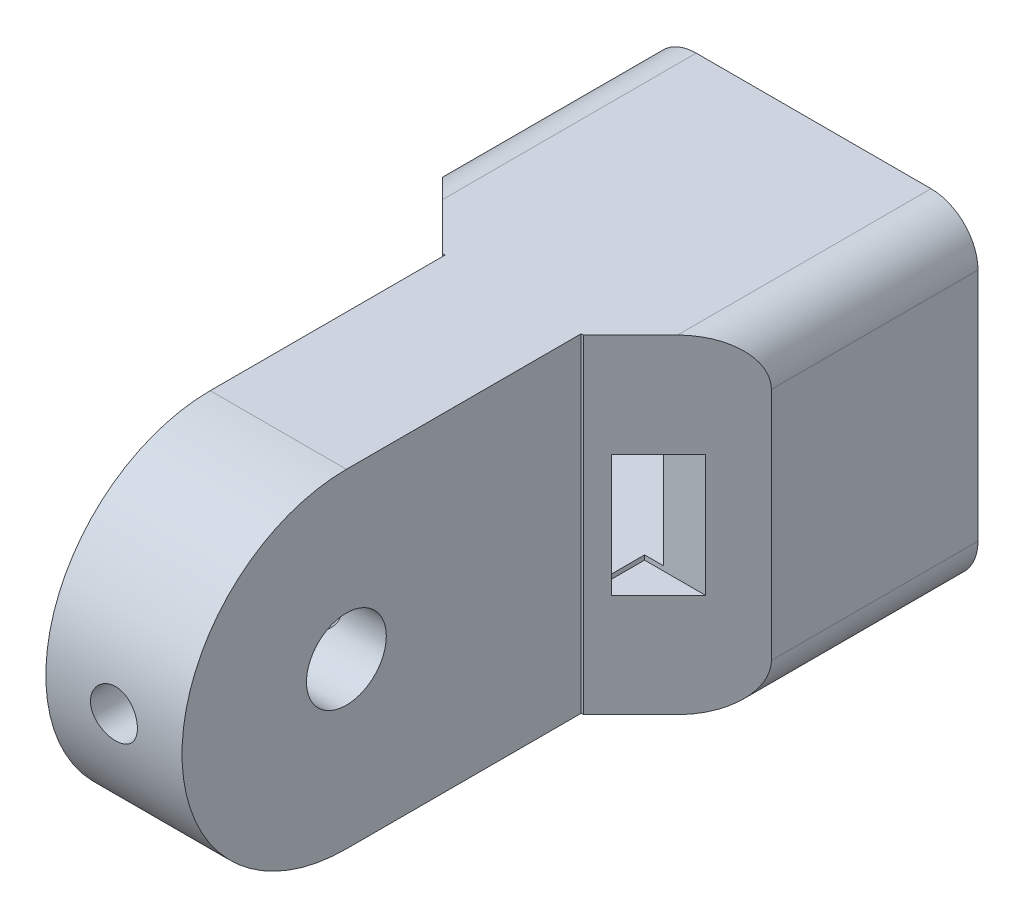
SolidWorks part; units mm, degrees
ref_plane "Alzado" through (0, 0, 0) normal (0, 0, 1) x (1, 0, 0)
ref_plane "Planta" through (0, 0, 0) normal (0, 1, 0) x (1, 0, 0)
ref_plane "Vista lateral" through (0, 0, 0) normal (1, 0, 0) x (0, 0, -1)
sketch "Croquis6" plane through (0, 0, 0) normal (1, 0, 0) x (0, 0, -1)
  line L0 (0, 17.5) -> (25, 17.5)
  line L1 (0, -17.5) -> (25, -17.5)
  line L2 (25, 17.5) -> (25, -17.5)
  circle A0 centre (0, 0) radius 4.25
  arc A1 (0, 17.5) -> (0, -17.5) centre (0, 0) ccw
  dimension "D1" = 8.5
  dimension "D2" = 35
  dimension "D3" = 25
extrude "Saliente-Extruir2" add sketch "Croquis6" along normal mid plane 14.5
sketch "Croquis7" plane through (0, 0, -25) normal (0, 0, -1) x (-1, 0, 0)
  line L1 (-17.5, -17.5) -> (17.5, -17.5)
  line L2 (-17.5, -17.5) -> (-17.5, 17.5)
  line L3 (-17.5, 17.5) -> (17.5, 17.5)
  line L4 (17.5, -17.5) -> (17.5, 17.5)
  line L5 (-17.5, -17.5) -> (17.5, 17.5) construction
  line L6 (-17.5, 17.5) -> (17.5, -17.5) construction
  point P0 (0, 0)
  dimension "D1" = 35
extrude "Saliente-Extruir3" add sketch "Croquis7" along normal blind 32
chamfer "Chaflán1" distance 10 angle 45 2 edges at (-17.5, 0, -25) (17.5, 0, -25)
sketch "Croquis8" plane through (0, 0, -57) normal (0, 0, -1) x (-1, 0, 0)
  line L1 (-5, -6.015) -> (5, -6.015) construction
  line L2 (-5, -6.015) -> (-5, 6.015) construction
  line L3 (-5, 6.015) -> (5, 6.015) construction
  line L4 (5, -6.015) -> (5, 6.015) construction
  line L5 (-5, -6.015) -> (5, 6.015) construction
  line L6 (-5, 6.015) -> (5, -6.015) construction
  line L7 (5, -6.015) -> (-9.5, -6.015)
  line L8 (5, -6.015) -> (5, 6.015)
  line L9 (5, 6.015) -> (-9.5, 6.015)
  line L10 (-9.5, -6.015) -> (-9.5, 6.015)
  line L11 (5, -6.015) -> (-9.5, 6.015) construction
  line L12 (5, 6.015) -> (-9.5, -6.015) construction
  point P0 (0, 0)
  point P6 (-2.25, 0)
  point P11 (0, 0)
  dimension "D1" = 10
  dimension "D2" = 12.03
  dimension "D3" = 14.5
  dimension "D4" = 12.03
  dimension "D5" = 5
extrude "Cortar-Extruir4" cut sketch "Croquis8" against normal blind 30.5
sketch "Croquis9" plane through (17.5, 0, 0) normal (1, 0, 0) x (0, 0, -1)
  line L0 (57, 17.5) -> (57, -17.5) construction
  line L1 (26.5, -6.5) -> (31.5, -6.5)
  line L2 (26.5, -6.5) -> (26.5, 6.5)
  line L3 (26.5, 6.5) -> (31.5, 6.5)
  line L4 (31.5, -6.5) -> (31.5, 6.5)
  line L5 (26.5, -6.5) -> (31.5, 6.5) construction
  line L6 (26.5, 6.5) -> (31.5, -6.5) construction
  point P0 (29, 0)
  point P5 (0, 0)
  dimension "D1" = 13
  dimension "D2" = 5
  dimension "D3" = 30.5
extrude "Cortar-Extruir5" cut sketch "Croquis9" against normal blind 10
fillet "Redondeo1" radius 5 4 edges at (-17.5, -17.5, -46) (-17.5, 17.5, -46) (17.5, -17.5, -46) (17.5, 17.5, -46)
sketch "Croquis10" plane through (0, 0, -57) normal (0, 0, -1) x (-1, 0, 0)
  circle A0 centre (-12.5, 12.5) radius 1.5
  circle A1 centre (12.5, 12.5) radius 1.5
  circle A2 centre (12.5, -12.5) radius 1.5
  circle A3 centre (-12.5, -12.5) radius 1.5
  point P12 (0, 0)
  dimension "D1" = 3
  dimension "D2" = 4
extrude "Cortar-Extruir6" cut sketch "Croquis10" against normal blind 10
ref_plane "Plano1" through (0, 0, 20) normal (0, 0, 1) x (1, 0, 0)
sketch "Croquis11" plane through (0, 0, 20) normal (0, 0, 1) x (1, 0, 0)
  circle A0 centre (0, 0) radius 2.5
  dimension "D1" = 5
extrude "Cortar-Extruir7" cut sketch "Croquis11" against normal blind 30
